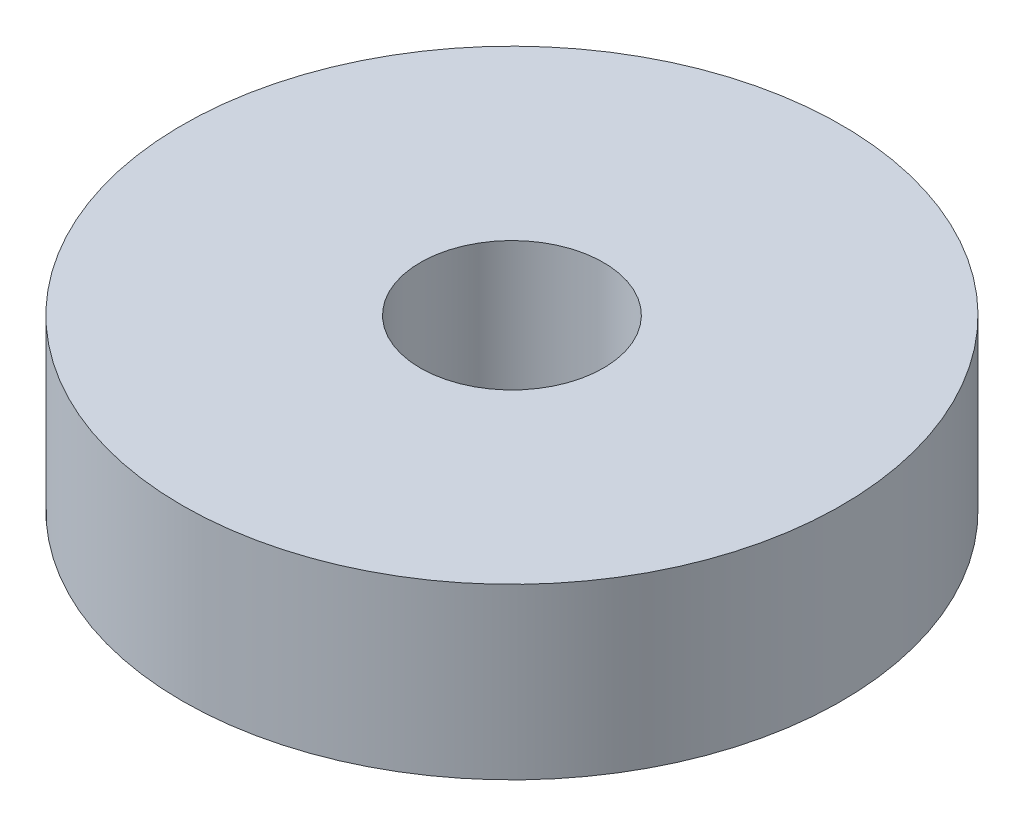
SolidWorks part; units mm, degrees
ref_plane "Front Plane" through (0, 0, 0) normal (0, 0, 1) x (1, 0, 0)
ref_plane "Top Plane" through (0, 0, 0) normal (0, 1, 0) x (1, 0, 0)
ref_plane "Right Plane" through (0, 0, 0) normal (1, 0, 0) x (0, 0, -1)
sketch "Sketch2" plane through (0, 0, 0) normal (0, 1, 0) x (1, 0, 0)
  circle A0 centre (0, 0) radius 18
  circle A1 centre (0, 0) radius 5
extrude "Boss-Extrude1" add sketch "Sketch2" along normal blind 9.25
